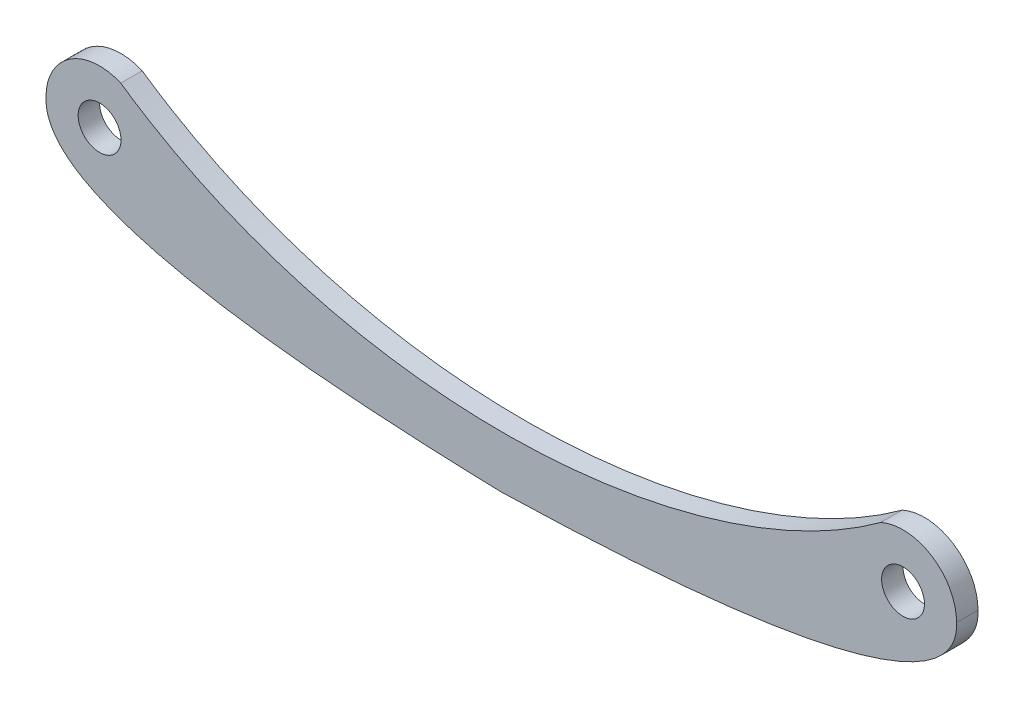
SolidWorks part; units mm, degrees
ref_plane "前视基准面" through (0, 0, 0) normal (0, 0, 1) x (1, 0, 0)
ref_plane "上视基准面" through (0, 0, 0) normal (0, 1, 0) x (1, 0, 0)
ref_plane "右视基准面" through (0, 0, 0) normal (1, 0, 0) x (0, 0, -1)
sketch "草图1" plane through (0, 0, 0) normal (0, 0, 1) x (1, 0, 0)
  line L0 (0, 0) -> (150, 0) construction
  line L4 (75, 0) -> (75, -30.7931) construction
  circle A0 centre (0, 0) radius 4
  circle A1 centre (150, 0) radius 4
  arc A2 (3.948, 9.1877) -> (-10, 0) centre (0, 0) ccw
  arc A3 (160, 0) -> (145.866, 9.1055) centre (150, 0) ccw
  spline S0 degree 3 poles (3.948, 9.1877) (46.9065, -20.3737) (110.5517, -16.707) (145.866, 9.1055) knots 0.022449 0.022449 0.022449 0.022449 0.850781 0.850781 0.850781 0.850781
  spline S1 degree 2 poles (-10, 0) (-10.8902, -19.1353) (75, -21.402) knots 0 0 0 1 1 1
  spline S2 degree 2 poles (160, 0) (160.8902, -19.1353) (75, -21.402) knots 0 0 0 1 1 1
  dimension "D1" = 150
extrude "凸台-拉伸1" add sketch "草图1" along normal blind 4
